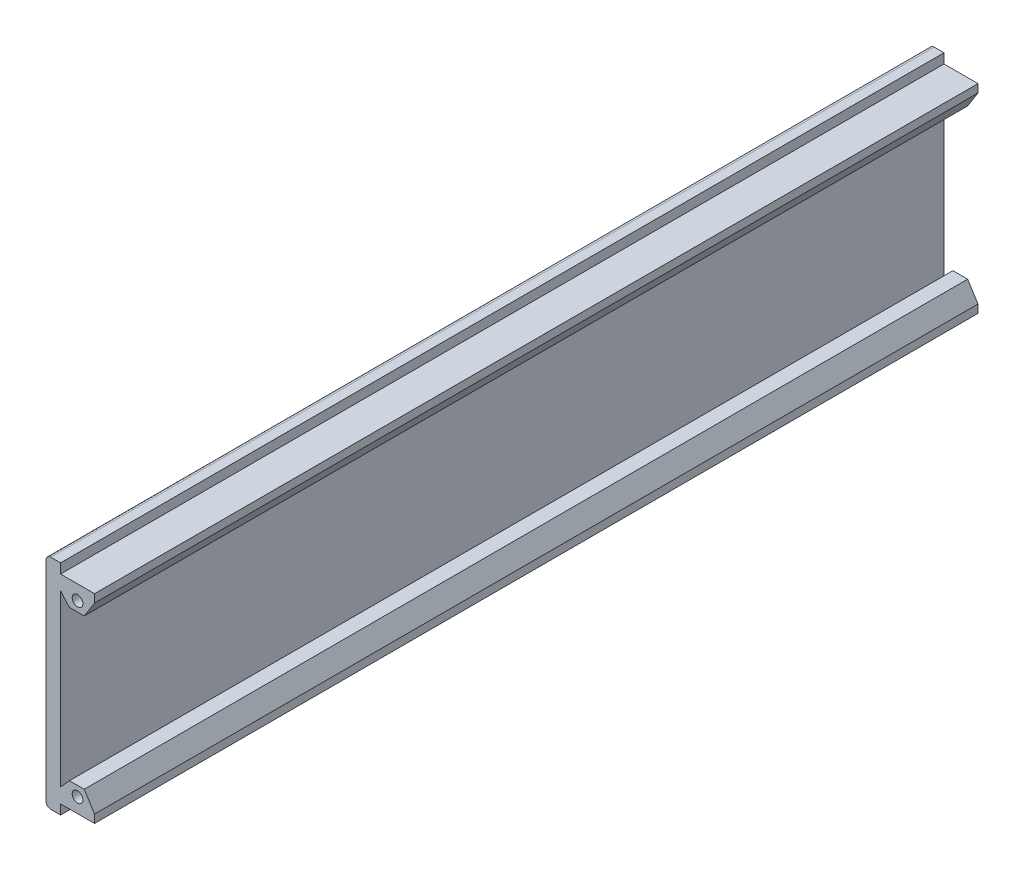
SolidWorks part; units mm, degrees
ref_plane "Front" through (0, 0, 0) normal (0, 0, 1) x (1, 0, 0)
ref_plane "Top" through (0, 0, 0) normal (0, 1, 0) x (1, 0, 0)
ref_plane "Right" through (0, 0, 0) normal (1, 0, 0) x (0, 0, -1)
sketch "草图1" plane through (0, 0, 0) normal (0, 0, 1) x (1, 0, 0)
  line L0 (3, 2) -> (10, 2)
  line L1 (1, 0) -> (3, 0)
  line L2 (0, 1) -> (0, 44)
  line L3 (0, 22.5) -> (3, 22.5) construction
  line L4 (3, 0) -> (3, 2)
  line L5 (10, 2) -> (10, 3.6758)
  line L6 (7.8735, 7.0452) -> (4.833, 7.0452)
  line L7 (7.8735, 37.9548) -> (4.833, 37.9548)
  line L8 (10, 43) -> (10, 41.3242)
  line L9 (1, 45) -> (3, 45)
  line L10 (3, 43) -> (10, 43)
  line L11 (6.5, 43) -> (6.5, 2) construction
  line L12 (10, 3.6758) -> (7.8735, 7.0452)
  line L13 (7.8735, 7.0452) -> (4.833, 7.0452)
  line L14 (4.833, 7.0452) -> (3, 5)
  line L15 (4.833, 37.9548) -> (3, 40)
  line L16 (10, 41.3242) -> (7.8735, 37.9548)
  line L17 (3, 5) -> (3, 40)
  line L18 (3, 43) -> (3, 45)
  arc A0 (1, 0) -> (0, 1) centre (1, 1) cw
  arc A1 (1, 45) -> (0, 44) centre (1, 44) ccw
  circle A2 centre (6.5, 5) radius 1.1029
  circle A3 centre (6.5, 40) radius 1.1029
  point P11 (0, 0)
  point P20 (0, 45)
  dimension "D2" = 1
  dimension "D1" = 3
  dimension "D3" = 2
  dimension "D4" = 41
  dimension "D5" = 3.5
  dimension "D6" = 7
  dimension "D7" = 35
extrude "凸台-拉伸1" add sketch "草图1" along normal blind 182 contours L9 A1 L2 A0 L1 L4 L0 L5 L12 L6 L14 L17 L15 L7 L16 L8 L10 L18 A2 A3
